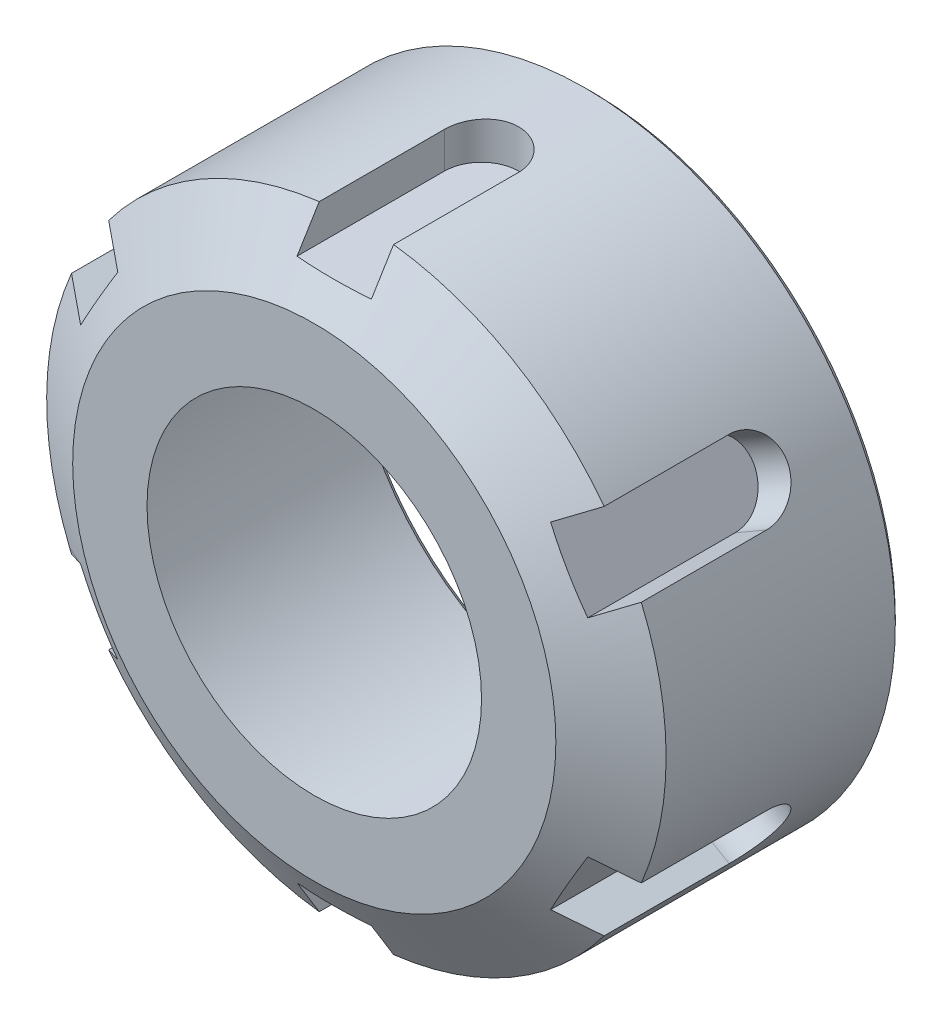
SolidWorks part; units mm, degrees
ref_plane "Спереди" through (0, 0, 0) normal (0, 0, 1) x (1, 0, 0)
ref_plane "Сверху" through (0, 0, 0) normal (0, 1, 0) x (1, 0, 0)
ref_plane "Справа" through (0, 0, 0) normal (1, 0, 0) x (0, 0, -1)
sketch "Эскиз1" plane through (0, 0, 0) normal (0, 1, 0) x (1, 0, 0)
  line L0 (0, 0) -> (0, 22.4) construction
  line L1 (19, 22.4) -> (25, 22.4)
  line L2 (25, 22.4) -> (25, 3.4)
  line L3 (25, 3.4) -> (19.5, 0)
  line L4 (19.5, 0) -> (13.5, 0)
  line L7 (19, 3.4) -> (19, 22.4)
  line L8 (13.5, 0) -> (19, 3.4)
  dimension "D1" = 25
  dimension "D2" = 22.4
  dimension "D3" = 19
  dimension "D4" = 19.5
  dimension "D5" = 13.5
  dimension "D6" = 19
revolve "Повернуть1" add sketch "Эскиз1" angle 360 about L0
sketch "Эскиз2" plane through (0, 0, 0) normal (0, 0, 1) x (1, 0, 0)
  line L0 (0, 0) -> (0, 36.3679) construction
  line L1 (-3, 26.3575) -> (3, 26.3575)
  line L2 (-3, 26.3575) -> (-3, 21.9)
  line L3 (-3, 21.9) -> (3, 21.9)
  line L4 (3, 26.3575) -> (3, 21.9)
  circle A0 centre (0, 0) radius 13.5 construction
  dimension "D1" = 3
  dimension "D2" = 3
  dimension "D3" = 21.9
extrude "Вырез-Вытянуть1" cut sketch "Эскиз2" against normal blind 13.5
sketch "Эскиз3" plane through (0, 0, -13.5) normal (0, 0, 1) x (1, 0, 0)
  line L0 (-3, 21.9) -> (3, 21.9) construction
  line L1 (3, 26.9) -> (0, 26.9)
  line L2 (3, 26.9) -> (3, 21.9)
  line L3 (3, 21.9) -> (0, 21.9)
  line L4 (0, 26.9) -> (0, 21.9)
  line L5 (3, 21.9) -> (3, 24.8193) construction
  dimension "D1" = 3
  dimension "D2" = 3
  dimension "D3" = 5
revolve "Вырез-Повернуть1" cut sketch "Эскиз3" angle 360 about L4
pattern_circular "Круговой массив1" count 6 over 360 about axis through (0, 0, 0) along (0, 0, 1) of "Вырез-Вытянуть1", "Вырез-Повернуть1"
chamfer "Фаска1" distance 0.5 angle 45 2 edges at (25, 0, -22.4) (19, 0, -22.4)
